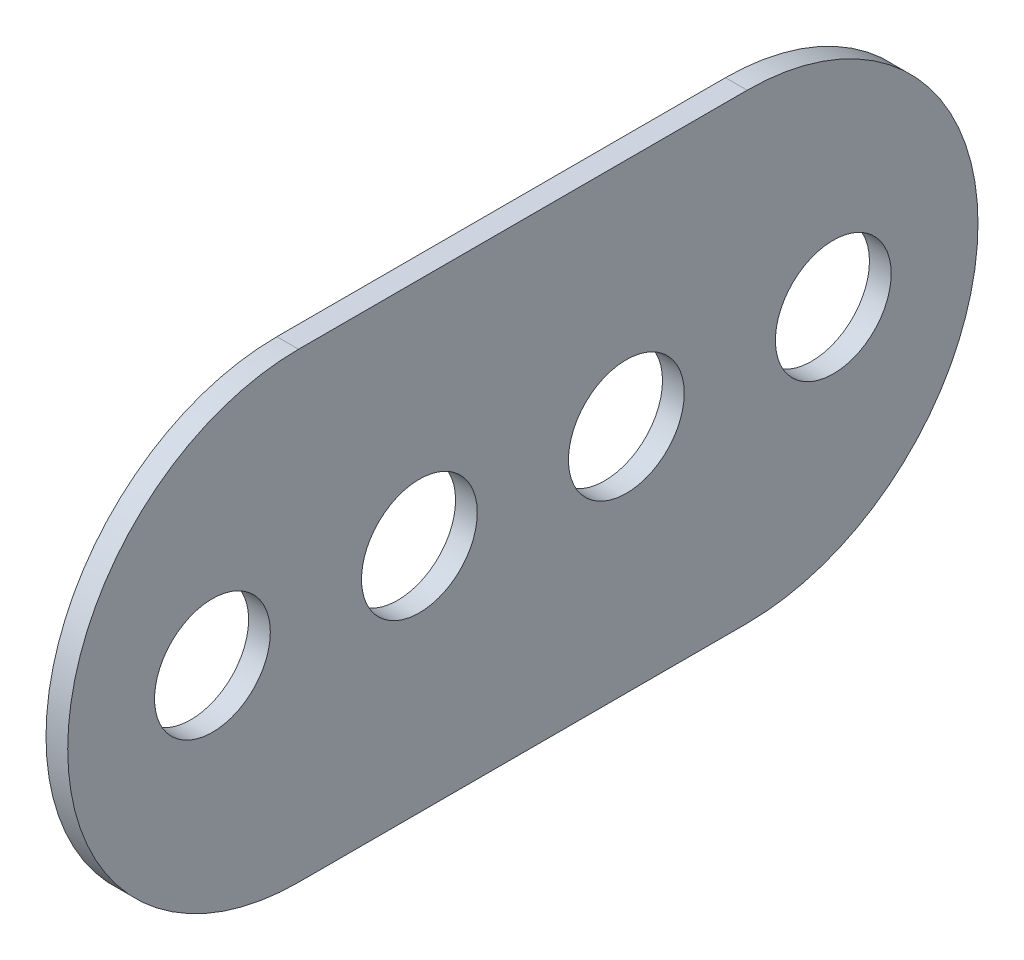
SolidWorks part; units mm, degrees
ref_plane "Front Plane" through (0, 0, 0) normal (0, 0, 1) x (1, 0, 0)
ref_plane "Top Plane" through (0, 0, 0) normal (0, 1, 0) x (1, 0, 0)
ref_plane "Right Plane" through (0, 0, 0) normal (1, 0, 0) x (0, 0, -1)
sketch "Sketch1" plane through (0, 0, 0) normal (1, 0, 0) x (0, 0, -1)
  line L0 (-31, 0) -> (31, 0) construction
  line L1 (-31, 32) -> (31, 32) construction
  line L2 (-31, -32) -> (31, -32) construction
  line L3 (-31, 31.9) -> (31, 31.9)
  line L4 (-31, -31.9) -> (31, -31.9)
  arc A0 (-31, 32) -> (-31, -32) centre (-31, 0) ccw construction
  arc A1 (31, -32) -> (31, 32) centre (31, 0) ccw construction
  arc A2 (31, -31.9) -> (31, 31.9) centre (31, 0) ccw
  arc A3 (-31, 31.9) -> (-31, -31.9) centre (-31, 0) ccw
  point P2 (0, 0)
  dimension "D1" = 64
  dimension "D2" = 62
  dimension "D3" = 0.1
extrude "Boss-Extrude1" add sketch "Sketch1" along normal mid plane 3
sketch "Sketch2" plane through (1.5, 0, 0) normal (1, 0, 0) x (0, 0, -1)
  line L0 (-42.9, 0) -> (-14.3, 0) construction
  line L1 (-14.3, 0) -> (14.3, 0) construction
  line L2 (14.3, 0) -> (42.9, 0) construction
  line L3 (-42.9, 0) -> (-62.9, 0) construction
  circle A0 centre (-14.3, 0) radius 8
  circle A1 centre (-42.9, 0) radius 8
  circle A2 centre (42.9, 0) radius 8
  circle A4 centre (14.3, 0) radius 8
  arc A5 (-31, 31.9) -> (-31, -31.9) centre (-31, 0) ccw construction
  point P2 (-50.9, 0)
  dimension "D1" = 16
  dimension "D2" = 12
extrude "Cut-Extrude1" cut sketch "Sketch2" against normal through all
